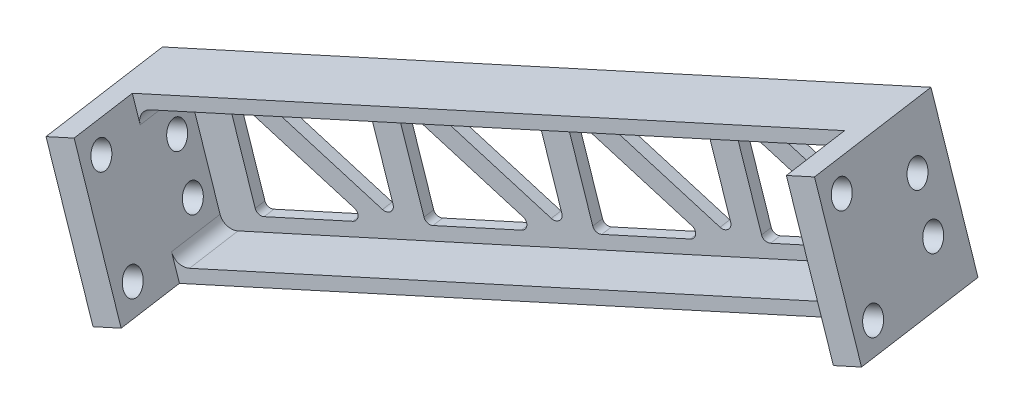
SolidWorks part; units mm, degrees
ref_plane "Front Plane" through (0, 0, 0) normal (0, 0, 1) x (1, 0, 0)
ref_plane "Top Plane" through (0, 0, 0) normal (0, 1, 0) x (1, 0, 0)
ref_plane "Right Plane" through (0, 0, 0) normal (1, 0, 0) x (0, 0, -1)
sketch3d "3DSketch1"
  line L0 (0, 0, 0) -> (-228.6, 0, 0) construction
  line L1 (-228.6, 0, 0) -> (-228.6, -76.2, 0) construction
  line L2 (-228.6, -76.2, 0) -> (-228.6, -76.2, 50.8) construction
  line L3 (-228.6, -76.2, 50.8) -> (0, 0, 0) construction
  line L4 (-228.6, -76.2, 50.8) -> (-209.3731, -69.791, 46.5274)
  line L5 (-209.3731, -69.791, 46.5274) -> (-17.2844, -5.7615, 3.841)
  line L6 (-17.2844, -5.7615, 3.841) -> (0, 0, 0)
  dimension "D1" = 228.6
  dimension "D2" = 76.2
  dimension "D3" = 50.8
ref_plane "Plane1" through (-17.2844, -5.7615, 3.841) normal (0.9283, 0.3094, -0.2063) x (-0.1957, -0.0652, -0.9785)
ref_plane "Plane2" through (-209.3731, -69.791, 46.5274) normal (0.9283, 0.3094, -0.2063) x (-0.1957, -0.0652, -0.9785)
sketch "Sketch1" plane through (-17.2844, -5.7615, 3.841) normal (0.9283, 0.3094, -0.2063) x (-0.1957, -0.0652, -0.9785)
  line L1 (19.05, 19.05) -> (-19.05, 19.05)
  line L2 (19.05, 19.05) -> (19.05, -19.05)
  line L3 (19.05, -19.05) -> (-19.05, -19.05)
  line L4 (-19.05, 19.05) -> (-19.05, -19.05)
  line L5 (19.05, 19.05) -> (-19.05, -19.05) construction
  line L6 (19.05, -19.05) -> (-19.05, 19.05) construction
  point P0 (0, 0)
  dimension "D1" = 38.1
extrude "Boss-Extrude1" add sketch "Sketch1" against normal blind 6.35
sketch "Sketch2" plane through (-23.179, -7.7263, 5.1509) normal (-0.9283, -0.3094, 0.2063) x (0.1957, 0.0652, 0.9785)
  line L0 (-19.05, 19.05) -> (0, 19.05)
  line L1 (-19.05, 19.05) -> (19.05, 19.05) construction
  line L2 (0, 19.05) -> (0, 15.875)
  line L3 (0, 15.875) -> (-15.875, 15.875)
  line L4 (-15.875, 15.875) -> (-15.875, -15.875)
  line L5 (-15.875, -15.875) -> (0, -15.875)
  line L6 (0, -15.875) -> (0, -19.05)
  line L7 (19.05, -19.05) -> (-19.05, -19.05) construction
  line L8 (0, -19.05) -> (-19.05, -19.05)
  line L9 (-19.05, -19.05) -> (-19.05, 19.05)
  dimension "D1" = 3.175
  dimension "D2" = 3.175
  dimension "D3" = 3.175
extrude "Boss-Extrude2" add sketch "Sketch2" along normal up to surface (167.1184 mm away)
sketch "Sketch3" plane through (-178.3115, -59.4372, 39.6248) normal (0.9283, 0.3094, -0.2063) x (-0.1957, -0.0652, -0.9785)
  line L1 (-19.05, -19.05) -> (19.05, -19.05)
  line L2 (-19.05, -19.05) -> (-19.05, 19.05)
  line L3 (-19.05, 19.05) -> (19.05, 19.05)
  line L4 (19.05, -19.05) -> (19.05, 19.05)
  line L5 (-19.05, -19.05) -> (19.05, 19.05) construction
  line L6 (-19.05, 19.05) -> (19.05, -19.05) construction
  point P0 (0, 0)
extrude "Boss-Extrude3" add sketch "Sketch3" along normal blind 6.35
fillet "Fillet1" radius 3.175 4 edges at (-168.9502, -73.0504, 30.5481) (-178.9904, -42.9298, 30.5481) (-19.7122, -23.3045, -2.6159) (-29.7524, 6.8162, -2.6159)
hole_wizard "1/4 (0.25) Diameter Hole1" positions "Sketch5" profile "Sketch6" hole size "1/4" standard "ANSI Inch"
sketch "Sketch5" plane through (-17.2844, -5.7615, 3.841) normal (0.9283, 0.3094, -0.2063) x (-0.1957, -0.0652, -0.9785)
  line L0 (19.05, 19.05) -> (-19.05, 19.05) construction
  line L1 (-19.05, -19.05) -> (19.05, -19.05) construction
  line L2 (-19.05, 19.05) -> (-19.05, -19.05) construction
  line L3 (19.05, -19.05) -> (19.05, 19.05) construction
  point P0 (-12.7, 12.7)
  point P2 (-12.7, -12.7)
  point P4 (9.525, 6.35)
  point P6 (9.525, -6.35)
  dimension "D1" = 12.7
  dimension "D2" = 12.7
  dimension "D3" = 6.35
  dimension "D4" = 6.35
  dimension "D5" = 6.35
  dimension "D6" = 9.525
sketch "Sketch6" plane through (-18.8151, 7.1153, 16.2678) normal (-0.0783, 0.7049, 0.7049) x (-0.3635, 0.6382, -0.6786)
  line L0 (0, 0) -> (0, 6.35)
  line L1 (0, 6.35) -> (3.175, 6.35)
  line L2 (3.175, 6.35) -> (3.175, 0)
  line L5 (3.175, 0) -> (0, 0)
  line L11 (0, -6.35) -> (0, 107.95) construction
  dimension "Thru Hole Dia." = 6.35
  dimension "Thru Hole Depth" = 6.35
hole_wizard "1/4 (0.25) Diameter Hole2" positions "Sketch8" profile "Sketch9" hole size "1/4" standard "ANSI Inch" end condition up to next
sketch "Sketch8" plane through (-178.3115, -59.4372, 39.6248) normal (-0.9283, -0.3094, 0.2063) x (0.1957, 0.0652, 0.9785)
  line L0 (19.05, 19.05) -> (-19.05, 19.05) construction
  line L1 (-19.05, -19.05) -> (19.05, -19.05) construction
  line L2 (19.05, 19.05) -> (19.05, -19.05) construction
  line L3 (-19.05, 19.05) -> (-19.05, -19.05) construction
  point P0 (12.7, 12.7)
  point P2 (12.7, -12.7)
  point P4 (-9.525, -6.35)
  point P6 (-9.525, 6.35)
  dimension "D1" = 6.35
  dimension "D2" = 6.35
  dimension "D3" = 6.35
  dimension "D4" = 12.7
  dimension "D5" = 12.7
  dimension "D6" = 9.525
sketch "Sketch9" plane through (-179.8422, -46.5604, 52.0516) normal (-0.0783, 0.7049, 0.7049) x (0.3635, -0.6382, 0.6786)
  line L0 (0, 0) -> (0, 6.35)
  line L1 (0, 6.35) -> (3.175, 6.35)
  line L2 (3.175, 6.35) -> (3.175, 0)
  line L5 (3.175, 0) -> (0, 0)
  line L11 (0, -6.35) -> (0, 107.95) construction
  dimension "Thru Hole Dia." = 6.35
  dimension "Thru Hole Depth" = 6.35
sketch "Sketch10" plane through (-3.1067, -1.0356, -15.5336) normal (0.1957, 0.0652, 0.9785) x (0.9807, -0.013, -0.1953)
  line L0 (-26.7874, -18.4932) -> (-33.2301, 0.4194)
  line L1 (-35.2448, 1.4102) -> (-54.1574, -5.0326)
  line L2 (-54.3461, -7.9598) -> (-28.9907, -20.4297)
  line L3 (-167.692, -73.8969) -> (-21.5223, -24.1026) construction
  line L4 (-177.9302, -43.8429) -> (-31.7605, 5.9513) construction
  line L5 (-19.5407, -20.0734) -> (-27.7313, 3.9698) construction
  line L6 (-35.0014, -22.4773) -> (-60.3569, -10.0075)
  line L7 (-62.5602, -11.9439) -> (-56.1174, -30.8566)
  line L8 (-54.1028, -31.8474) -> (-35.1901, -25.4046)
  line L9 (-57.7852, -6.2684) -> (-63.796, -8.3161) construction
  line L10 (-62.8521, -30.7791) -> (-69.2949, -11.8664)
  line L11 (-71.3095, -10.8756) -> (-90.2222, -17.3184)
  line L12 (-90.4109, -20.2457) -> (-65.0554, -32.7155)
  line L13 (-71.0662, -34.7632) -> (-96.4217, -22.2933)
  line L14 (-98.625, -24.2298) -> (-92.1822, -43.1424)
  line L15 (-90.1676, -44.1332) -> (-71.2549, -37.6904)
  line L16 (-93.85, -18.5543) -> (-99.8608, -20.6019) construction
  line L17 (-98.9169, -43.0649) -> (-105.3597, -24.1523)
  line L18 (-107.3743, -23.1615) -> (-126.287, -29.6043)
  line L19 (-126.4756, -32.5315) -> (-101.1202, -45.0014)
  line L20 (-107.131, -47.049) -> (-132.4864, -34.5791)
  line L21 (-134.6897, -36.5156) -> (-128.2469, -55.4282)
  line L22 (-126.2323, -56.419) -> (-107.3197, -49.9762)
  line L23 (-129.9148, -30.8401) -> (-135.9256, -32.8878) construction
  line L24 (-134.9817, -55.3507) -> (-141.4245, -36.4381)
  line L25 (-143.4391, -35.4473) -> (-162.3517, -41.8901)
  line L26 (-162.5404, -44.8173) -> (-137.185, -57.2872)
  line L27 (-143.1958, -59.3348) -> (-168.5512, -46.865)
  line L28 (-170.7545, -48.8014) -> (-164.3117, -67.7141)
  line L29 (-162.2971, -68.7049) -> (-143.3845, -62.2621)
  line L30 (-165.9796, -43.1259) -> (-171.9904, -45.1736) construction
  arc A0 (-33.2301, 0.4194) -> (-35.2448, 1.4102) centre (-34.7328, -0.0925) ccw
  arc A1 (-54.1574, -5.0326) -> (-54.3461, -7.9598) centre (-53.6455, -6.5353) ccw
  arc A2 (-60.3569, -10.0075) -> (-62.5602, -11.9439) centre (-61.0575, -11.432) ccw
  arc A3 (-35.1901, -25.4046) -> (-35.0014, -22.4773) centre (-35.702, -23.9019) ccw
  arc A4 (-56.1174, -30.8566) -> (-54.1028, -31.8474) centre (-54.6147, -30.3447) ccw
  arc A5 (-26.7874, -18.4932) -> (-28.9907, -20.4297) centre (-28.2901, -19.0051) cw
  arc A6 (-69.2949, -11.8664) -> (-71.3095, -10.8756) centre (-70.7976, -12.3783) ccw
  arc A7 (-90.2222, -17.3184) -> (-90.4109, -20.2457) centre (-89.7103, -18.8211) ccw
  arc A8 (-96.4217, -22.2933) -> (-98.625, -24.2298) centre (-97.1223, -23.7178) ccw
  arc A9 (-71.2549, -37.6904) -> (-71.0662, -34.7632) centre (-71.7668, -36.1877) ccw
  arc A10 (-92.1822, -43.1424) -> (-90.1676, -44.1332) centre (-90.6795, -42.6305) ccw
  arc A11 (-62.8521, -30.7791) -> (-65.0554, -32.7155) centre (-64.3548, -31.291) cw
  arc A12 (-105.3597, -24.1523) -> (-107.3743, -23.1615) centre (-106.8624, -24.6642) ccw
  arc A13 (-126.287, -29.6043) -> (-126.4756, -32.5315) centre (-125.7751, -31.107) ccw
  arc A14 (-132.4864, -34.5791) -> (-134.6897, -36.5156) centre (-133.187, -36.0037) ccw
  arc A15 (-107.3197, -49.9762) -> (-107.131, -47.049) centre (-107.8316, -48.4735) ccw
  arc A16 (-128.2469, -55.4282) -> (-126.2323, -56.419) centre (-126.7442, -54.9163) ccw
  arc A17 (-98.9169, -43.0649) -> (-101.1202, -45.0014) centre (-100.4196, -43.5768) cw
  arc A18 (-141.4245, -36.4381) -> (-143.4391, -35.4473) centre (-142.9272, -36.95) ccw
  arc A19 (-162.3517, -41.8901) -> (-162.5404, -44.8173) centre (-161.8398, -43.3928) ccw
  arc A20 (-168.5512, -46.865) -> (-170.7545, -48.8014) centre (-169.2518, -48.2895) ccw
  arc A21 (-143.3845, -62.2621) -> (-143.1958, -59.3348) centre (-143.8964, -60.7594) ccw
  arc A22 (-164.3117, -67.7141) -> (-162.2971, -68.7049) centre (-162.809, -67.2022) ccw
  arc A23 (-134.9817, -55.3507) -> (-137.185, -57.2872) centre (-136.4844, -55.8626) cw
  point P14 (-33.7421, 1.9221)
  point P27 (-25.5515, -22.1211)
  dimension "D6" = 1.5875
  dimension "D1" = 25.4
  dimension "D2" = 3.175
  dimension "D3" = 6.35
  dimension "D4" = 3.175
  dimension "D5" = 6.35
  dimension "D7" = 4
extrude "Cut-Extrude1" cut sketch "Sketch10" against normal up to next
